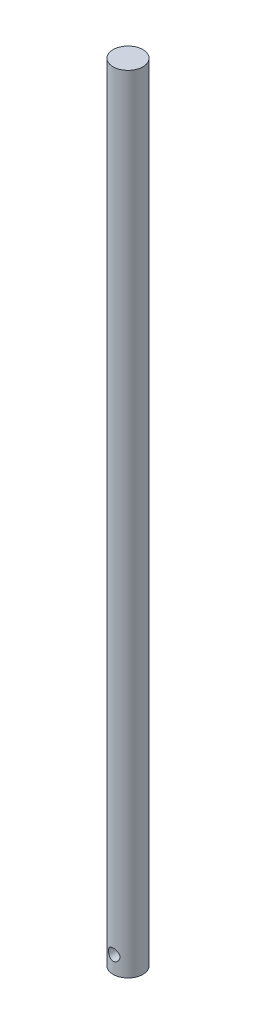
SolidWorks part; units mm, degrees
ref_plane "Front Plane" through (0, 0, 0) normal (0, 0, 1) x (1, 0, 0)
ref_plane "Top Plane" through (0, 0, 0) normal (0, 1, 0) x (1, 0, 0)
ref_plane "Right Plane" through (0, 0, 0) normal (1, 0, 0) x (0, 0, -1)
sketch "Sketch1" plane through (0, 0, 0) normal (0, 1, 0) x (1, 0, 0)
  circle A0 centre (0, 0) radius 13
  dimension "D1" = 26
extrude "Boss-Extrude1" add sketch "Sketch1" along normal blind 685
sketch "Sketch2" plane through (0, 0, 0) normal (0, 0, 1) x (1, 0, 0)
  line L0 (0, 0) -> (0, 15) construction
  circle A0 centre (0, 15) radius 5
  dimension "D1" = 15
extrude "Cut-Extrude1" cut sketch "Sketch2" against normal through all and the other way through all
